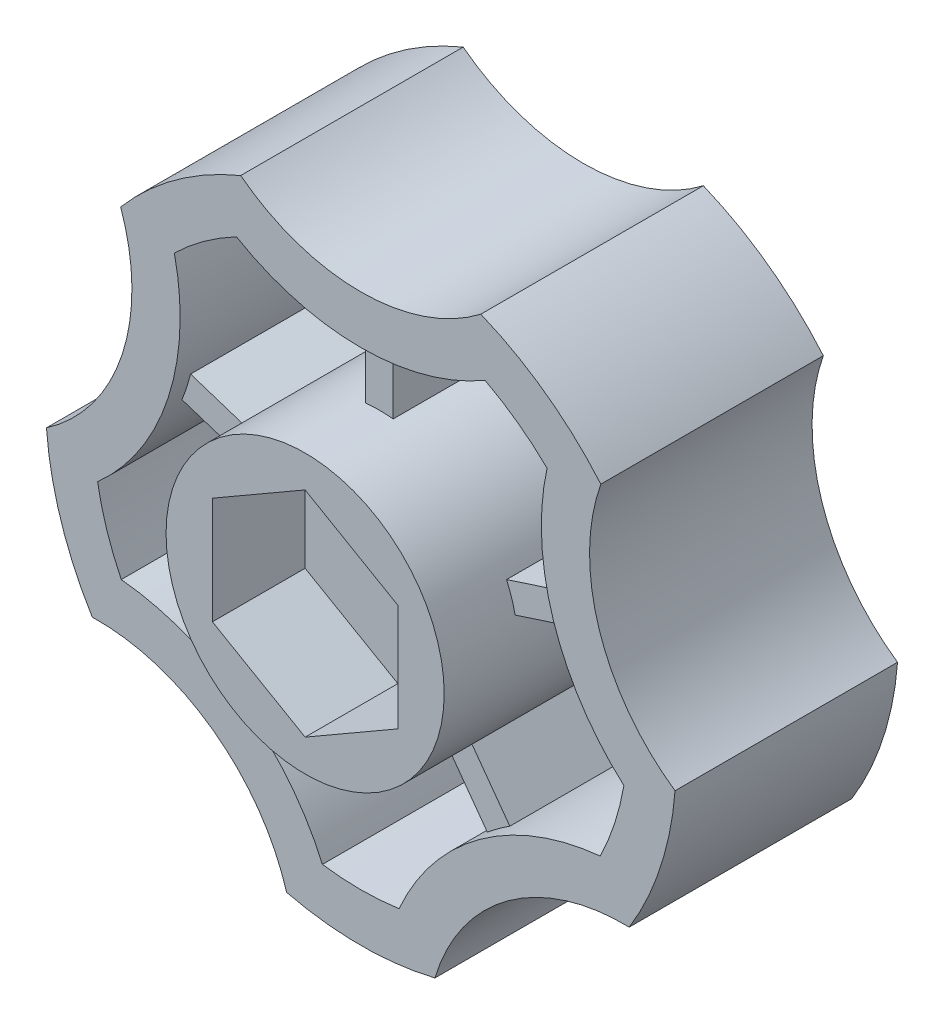
SolidWorks part; units mm, degrees
ref_plane "Plan de face" through (0, 0, 0) normal (0, 0, 1) x (1, 0, 0)
ref_plane "Plan de dessus" through (0, 0, 0) normal (0, 1, 0) x (1, 0, 0)
ref_plane "Plan de droite" through (0, 0, 0) normal (1, 0, 0) x (0, 0, -1)
sketch "Esquisse1" plane through (0, 0, 0) normal (0, 0, 1) x (1, 0, 0)
  line L0 (0, 0) -> (0, 58.3015) construction
  line L1 (0, 0) -> (-42.3089, 58.2332) construction
  line L2 (0, 0) -> (35.9888, 49.5343) construction
  arc A0 (-6.4757, 15.7183) -> (-12.9479, 11.016) centre (0, 0) ccw
  arc A1 (-6.4757, 15.7183) -> (6.4757, 15.7183) centre (0, 24.1721) ccw
  arc A2 (12.9479, 11.016) -> (16.9501, -1.3016) centre (22.9891, 7.4696) ccw
  arc A3 (14.478, -8.91) -> (4, -16.5227) centre (14.208, -19.5557) ccw
  arc A4 (-4, -16.5227) -> (-14.478, -8.91) centre (-14.208, -19.5557) ccw
  arc A5 (-16.9501, -1.3016) -> (-12.9479, 11.016) centre (-22.9891, 7.4696) ccw
  arc A6 (-16.9501, -1.3016) -> (-14.478, -8.91) centre (0, 0) ccw
  arc A7 (-4, -16.5227) -> (4, -16.5227) centre (0, 0) ccw
  arc A8 (14.478, -8.91) -> (16.9501, -1.3016) centre (0, 0) ccw
  arc A9 (12.9479, 11.016) -> (6.4757, 15.7183) centre (0, 0) ccw
  dimension "D1" = 34
  dimension "D2" = 72
  dimension "D3" = 36
  dimension "D4" = 4
  dimension "D5" = 5
extrude "Boss.-Extru.1" add sketch "Esquisse1" along normal blind 12
shell "Coque1" thickness 2.6
ref_plane "Plan1" through (0, 0, 15) normal (0, 0, 1) x (1, 0, 0)
sketch "Esquisse4" plane through (0, 0, 15) normal (0, 0, 1) x (1, 0, 0)
  circle A0 centre (0, 0) radius 7.5
  dimension "D1" = 15
extrude "Boss.-Extru.2" add sketch "Esquisse4" against normal up to surface (12.4 mm away) up to face at (0, 0, 2.6)
ref_plane "Plan2" through (0, 0, 11) normal (0, 0, 1) x (1, 0, 0)
sketch "Esquisse6" plane through (0, 0, 11) normal (0, 0, 1) x (1, 0, 0)
  line L0 (0, 12.4387) -> (0, 5.8672)
rib "Nervure1" sketch "Esquisse6" sketch "Esquisse6" thickness 1.5 extrusion direction normal to sketch draft on no parameters "D1"=1.5
pattern_circular "Répétition circulaire1" count 5 over 360 about axis through (0, 0, 0) along (0, 0, 1) of "Nervure1"
sketch "Esquisse7" plane through (0, 0, 0) normal (0, 0, -1) x (-1, 0, 0)
  circle A0 centre (0, 0) radius 6
  dimension "D1" = 12
extrude "Enlèv. mat.-Extru.1" cut sketch "Esquisse7" against normal blind 4.5
sketch "Esquisse8" plane through (0, 0, 15) normal (0, 0, 1) x (1, 0, 0)
  line L6 (-5, 2.8868) -> (-5, -2.8868)
  line L7 (0, 5.7735) -> (-5, 2.8868)
  line L8 (5, 2.8868) -> (0, 5.7735)
  line L9 (5, -2.8868) -> (5, 2.8868)
  line L10 (0, -5.7735) -> (5, -2.8868)
  line L11 (-5, -2.8868) -> (0, -5.7735)
  line L12 (-5, 2.8868) -> (-5, -2.8868)
  line L13 (0, 5.7735) -> (-5, 2.8868)
  line L14 (5, 2.8868) -> (0, 5.7735)
  line L15 (5, -2.8868) -> (5, 2.8868)
  line L16 (0, -5.7735) -> (5, -2.8868)
  line L17 (-5, -2.8868) -> (0, -5.7735)
  dimension "D1" = 0
extrude "Enlèv. mat.-Extru.2" cut sketch "Esquisse8" against normal blind 5
